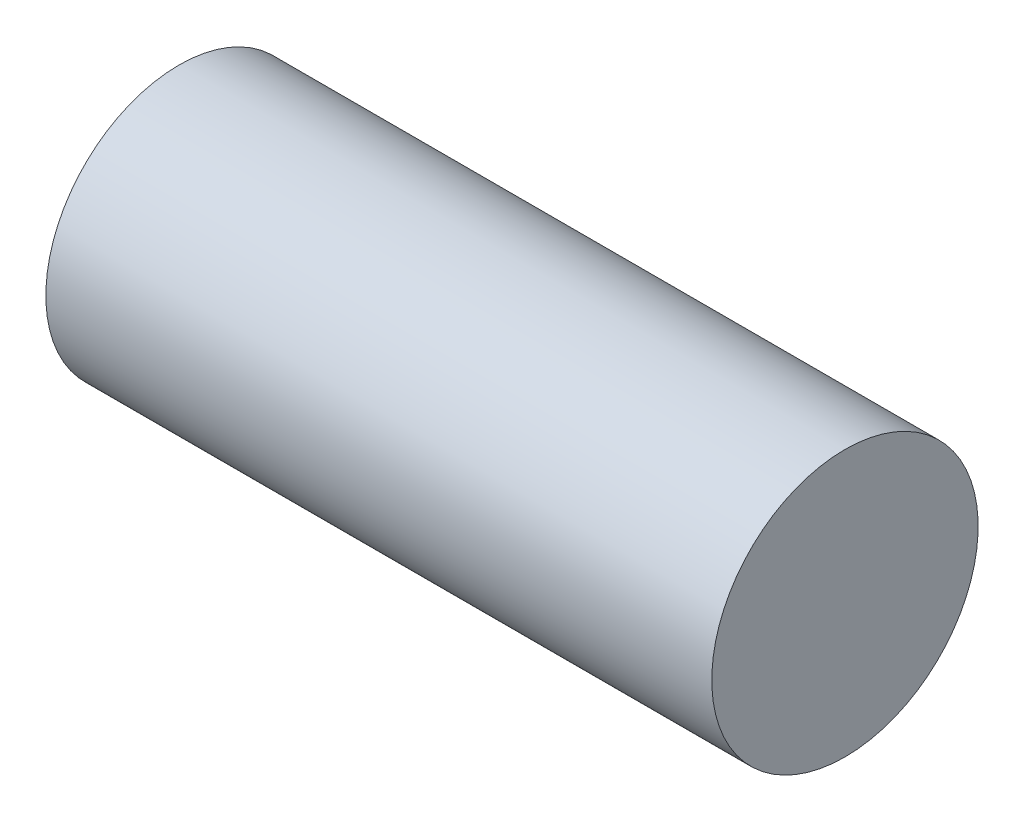
SolidWorks part; units mm, degrees
ref_plane "正面" through (0, 0, 0) normal (0, 0, 1) x (1, 0, 0)
ref_plane "平面" through (0, 0, 0) normal (0, 1, 0) x (1, 0, 0)
ref_plane "右側面" through (0, 0, 0) normal (1, 0, 0) x (0, 0, -1)
sketch "ｽｹｯﾁ1" plane through (0, 0, 0) normal (0, 0, 1) x (1, 0, 0)
  line L0 (0, 0) -> (0, -60)
  line L1 (0, -60) -> (300, -60)
  line L2 (150, -60) -> (150, -10)
  line L3 (160, -10) -> (140, -10)
  line L4 (140, -10) -> (100, -50)
  line L5 (100, -50) -> (10, -50)
  line L6 (10, -50) -> (10, 0)
  line L7 (10, 0) -> (0, 0)
  line L8 (290, 0) -> (300, 0)
  line L9 (290, -50) -> (290, 0)
  line L10 (200, -50) -> (290, -50)
  line L11 (160, -10) -> (200, -50)
  line L12 (300, 0) -> (300, -60)
  dimension "D1" = 150
  dimension "D2" = 60
  dimension "D3" = 50
  dimension "D4" = 50
  dimension "D5" = 45
  dimension "D6" = 10
  dimension "D7" = 10
revolve "回転1" add sketch "ｽｹｯﾁ1" angle 360 about L7
